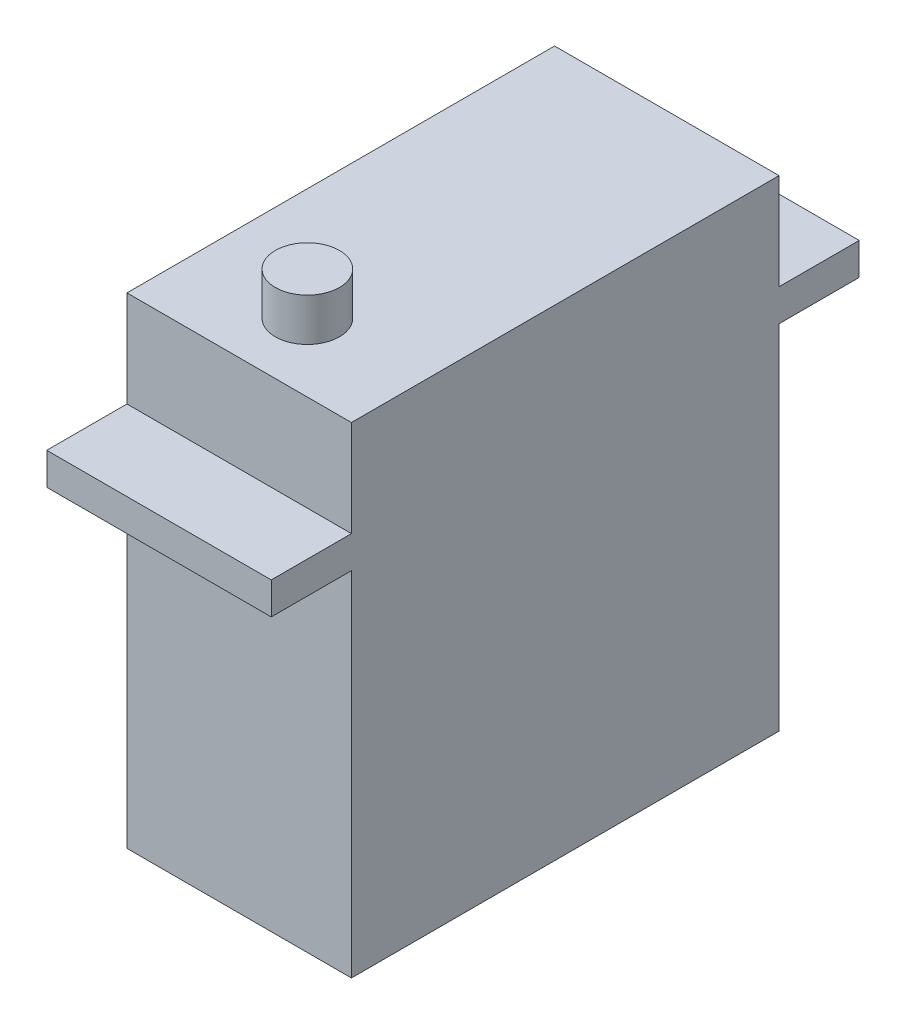
SolidWorks part; units mm, degrees
ref_plane "Front Plane" through (0, 0, 0) normal (0, 0, 1) x (1, 0, 0)
ref_plane "Top Plane" through (0, 0, 0) normal (0, 1, 0) x (1, 0, 0)
ref_plane "Right Plane" through (0, 0, 0) normal (1, 0, 0) x (0, 0, -1)
sketch "Sketch1" plane through (0, 0, 0) normal (0, 1, 0) x (1, 0, 0)
  line L1 (-10.5, -20) -> (10.5, -20)
  line L2 (-10.5, -20) -> (-10.5, 20)
  line L3 (-10.5, 20) -> (10.5, 20)
  line L4 (10.5, -20) -> (10.5, 20)
  line L5 (-10.5, -20) -> (10.5, 20) construction
  line L6 (-10.5, 20) -> (10.5, -20) construction
  point P0 (0, 0)
  dimension "D1" = 21
  dimension "D2" = 40
extrude "Boss-Extrude1" add sketch "Sketch1" along normal blind 45
sketch "Sketch2" plane through (0, 0, 20) normal (0, 0, 1) x (1, 0, 0)
  line L0 (-10.5, 45) -> (-10.5, 0) construction
  line L1 (-10.5, 36) -> (10.5, 36)
  line L2 (-10.5, 36) -> (-10.5, 33)
  line L3 (-10.5, 33) -> (10.5, 33)
  line L4 (10.5, 36) -> (10.5, 33)
  line L5 (10.5, 45) -> (10.5, 0) construction
  line L6 (11.55, 0) -> (-11.55, 0) construction
  dimension "D1" = 33
  dimension "D2" = 3
extrude "Boss-Extrude2" add sketch "Sketch2" along normal blind 7.5
sketch "Sketch3" plane through (0, 0, -20) normal (0, 0, -1) x (-1, 0, 0)
  line L1 (-10.5, 36) -> (10.5, 36)
  line L2 (-10.5, 36) -> (-10.5, 33)
  line L3 (-10.5, 33) -> (10.5, 33)
  line L4 (10.5, 36) -> (10.5, 33)
extrude "Boss-Extrude3" add sketch "Sketch3" along normal blind 7.5
sketch "Sketch5" plane through (0, 45, 0) normal (0, 1, 0) x (1, 0, 0)
  line L0 (0, -24.75) -> (0, 24.75) construction
  circle A0 centre (0, -13.6202) radius 3
extrude "Boss-Extrude4" add sketch "Sketch5" along normal blind 4
